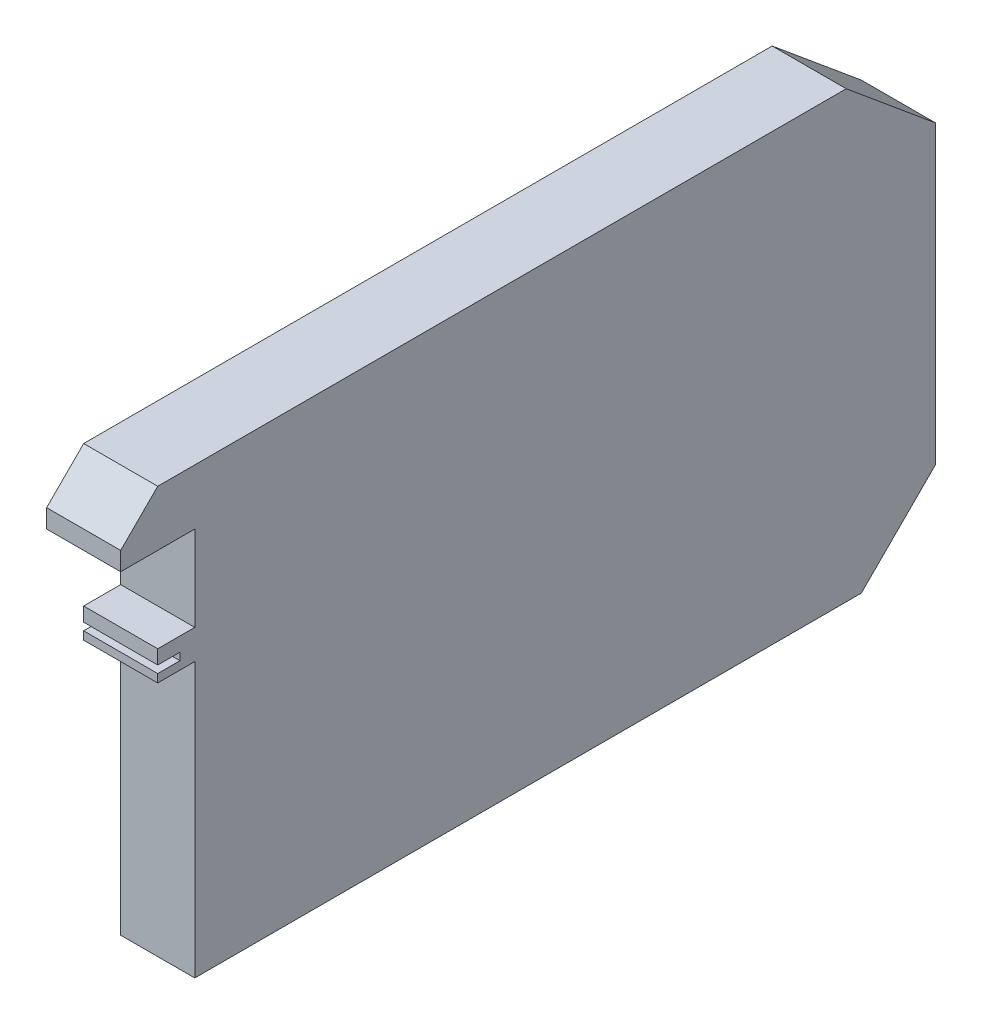
SolidWorks part; units mm, degrees
ref_plane "Front Plane" through (0, 0, 0) normal (0, 0, 1) x (1, 0, 0)
ref_plane "Top Plane" through (0, 0, 0) normal (0, 1, 0) x (1, 0, 0)
ref_plane "Right Plane" through (0, 0, 0) normal (1, 0, 0) x (0, 0, -1)
sketch "Sketch1" plane through (0, 0, 0) normal (1, 0, 0) x (0, 0, -1)
  line L0 (-22.9235, 18.6228) -> (-22.9235, -36.3772)
  line L1 (-22.9235, -36.3772) -> (67.0765, -36.3772)
  line L2 (77.0765, -26.3772) -> (77.0765, 13.6228)
  line L3 (77.0765, 13.6228) -> (65.0412, 23.6228)
  line L4 (65.0412, 23.6228) -> (-14.9588, 23.6228)
  line L5 (-14.9588, 23.6228) -> (-22.9235, 18.6228)
  line L6 (77.0765, -26.3772) -> (67.0765, -36.3772)
  dimension "D1" = 10
  dimension "D2" = 40
  dimension "D3" = 80
  dimension "D4" = 55
  dimension "D5" = 5
  dimension "D6" = 100
  dimension "D7" = 90
extrude "Boss-Extrude1" add sketch "Sketch1" against normal blind 10
sketch "Sketch2" plane through (0, 0, 22.9235) normal (0, 0, 1) x (1, 0, 0)
  line L0 (0, 18.6228) -> (0, -36.3772) construction
  line L1 (-10, 4.6228) -> (0, 4.6228)
  line L2 (-10, 4.6228) -> (-10, 0.6228)
  line L3 (-10, 0.6228) -> (0, 0.6228)
  line L4 (0, 4.6228) -> (0, 0.6228)
  line L5 (-10, 4.6228) -> (0, 0.6228) construction
  line L6 (-10, 0.6228) -> (0, 4.6228) construction
  line L7 (-10, 18.6228) -> (-10, -36.3772) construction
  line L8 (-10, -36.3772) -> (0, -36.3772) construction
  point P0 (-5, 2.6228)
  dimension "D1" = 39
  dimension "D2" = 4
extrude "Boss-Extrude2" add sketch "Sketch2" along normal blind 5
sketch "Sketch3" plane through (0, 0, 22.9235) normal (0, 0, 1) x (1, 0, 0)
  line L1 (-10, 23.6228) -> (0, 23.6228)
  line L2 (-10, 23.6228) -> (-10, 16.1228)
  line L3 (-10, 16.1228) -> (0, 16.1228)
  line L4 (0, 23.6228) -> (0, 16.1228)
  line L5 (-10, 23.6228) -> (0, 16.1228) construction
  line L6 (-10, 16.1228) -> (0, 23.6228) construction
  line L7 (-10, -36.3772) -> (0, -36.3772) construction
  point P0 (-5, 19.8728)
  dimension "D1" = 52.5
extrude "Boss-Extrude3" add sketch "Sketch3" along normal mid plane 20
chamfer "Chamfer1" distance 5 angle 45 1 edges at (-5, 23.6228, 32.9235)
sketch "Sketch4" plane through (0, 0, 0) normal (1, 0, 0) x (0, 0, -1)
  line L0 (-27.9235, 4.6228) -> (-22.9235, 4.6228) construction
  line L1 (-27.9235, 2.7228) -> (-24.9235, 2.7228)
  line L2 (-27.9235, 2.7228) -> (-27.9235, 1.7228)
  line L3 (-27.9235, 1.7228) -> (-24.9235, 1.7228)
  line L4 (-24.9235, 2.7228) -> (-24.9235, 1.7228)
  line L5 (-27.9235, 2.7228) -> (-24.9235, 1.7228) construction
  line L6 (-27.9235, 1.7228) -> (-24.9235, 2.7228) construction
  line L7 (-27.9235, 0.6228) -> (-27.9235, 4.6228) construction
  point P0 (-26.4235, 2.2228)
  dimension "D1" = 1.9
  dimension "D2" = 3
  dimension "D3" = 1
  dimension "D4" = 0
extrude "Cut-Extrude1" cut sketch "Sketch4" against normal blind 10
